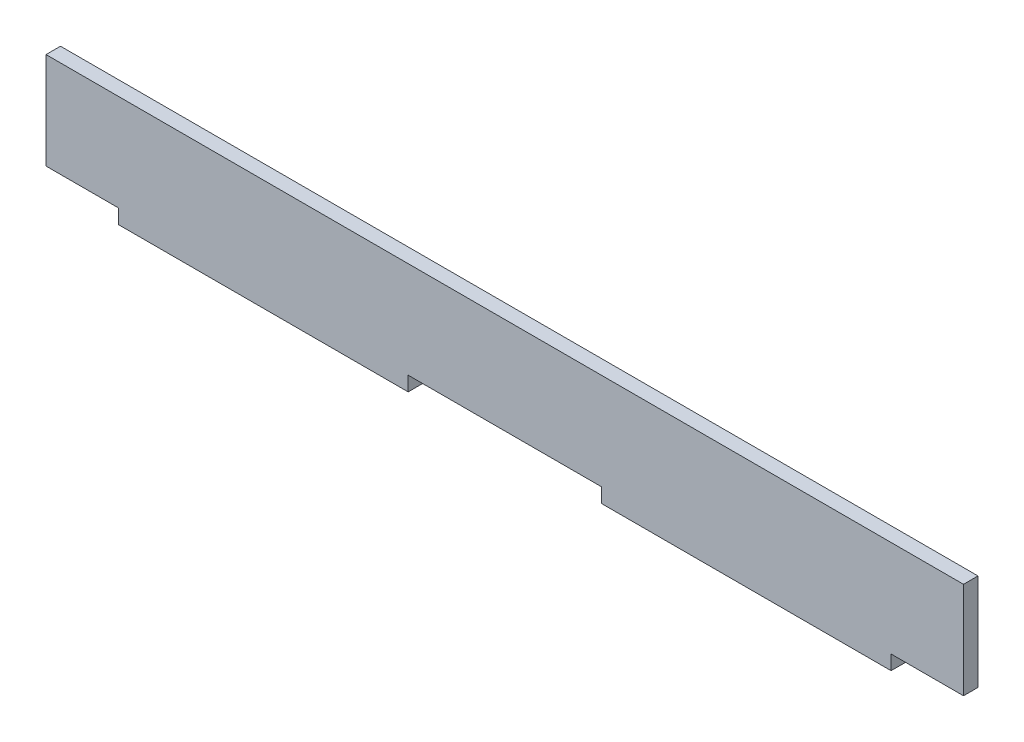
SolidWorks part; units mm, degrees
ref_plane "Plan de face" through (0, 0, 0) normal (0, 0, 1) x (1, 0, 0)
ref_plane "Plan de dessus" through (0, 0, 0) normal (0, 1, 0) x (1, 0, 0)
ref_plane "Plan de droite" through (0, 0, 0) normal (1, 0, 0) x (0, 0, -1)
sketch "Esquisse1" plane through (0, 0, 0) normal (0, 0, 1) x (1, 0, 0)
  line L0 (175, 0) -> (190, 0)
  line L1 (0, 0) -> (15, 0)
  line L2 (0, 0) -> (0, 20)
  line L3 (0, 20) -> (190, 20)
  line L4 (190, 0) -> (190, 20)
  line L14 (175, 0) -> (175, -3)
  line L15 (175, -3) -> (115, -3)
  line L16 (115, 0) -> (115, -3)
  line L17 (95, 20) -> (95, 0) construction
  line L18 (15, 0) -> (15, -3)
  line L19 (75, 0) -> (75, -3)
  line L20 (15, -3) -> (75, -3)
  line L21 (75, 0) -> (115, 0)
  dimension "D1" = 190
  dimension "D2" = 20
  dimension "D4" = 60
  dimension "D5" = 3
  dimension "D6" = 40
extrude "Boss.-Extru.1" add sketch "Esquisse1" along normal blind 3
